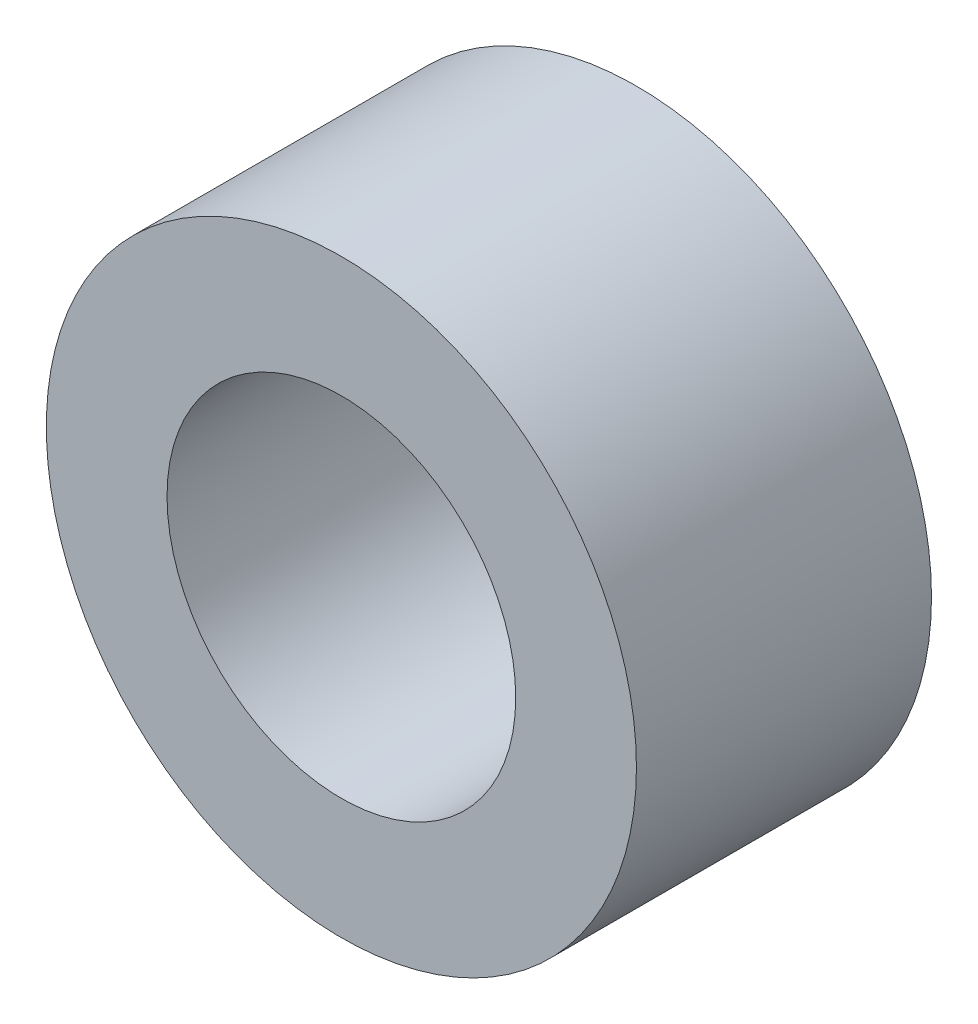
SolidWorks part; units mm, degrees
ref_plane "正面" through (0, 0, 0) normal (0, 0, 1) x (1, 0, 0)
ref_plane "平面" through (0, 0, 0) normal (0, 1, 0) x (1, 0, 0)
ref_plane "右側面" through (0, 0, 0) normal (1, 0, 0) x (0, 0, -1)
sketch "ｽｹｯﾁ1" plane through (0, 0, 0) normal (0, 0, 1) x (1, 0, 0)
  circle A0 centre (0, 0) radius 11
  circle A1 centre (0, 0) radius 6.5
  dimension "D1" = 13
  dimension "D2" = 22
extrude "ﾎﾞｽ - 押し出し1" add sketch "ｽｹｯﾁ1" along normal blind 11
